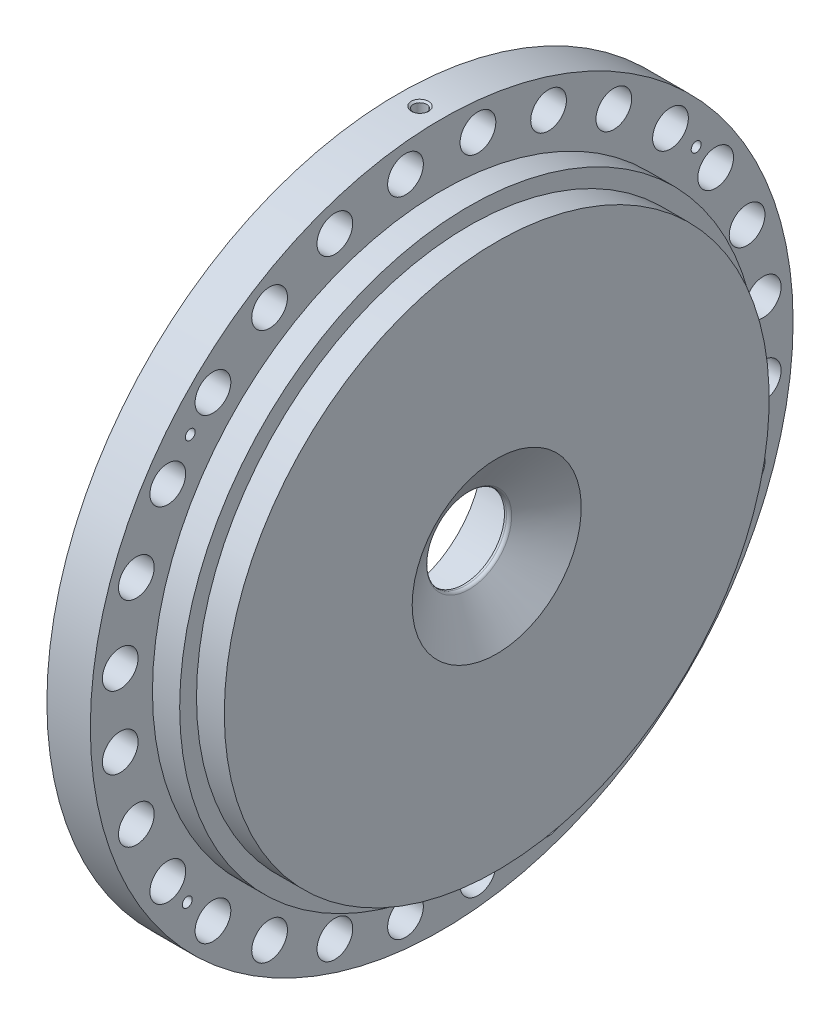
SolidWorks part; units mm, degrees
other "Markup1"
sketch "Sketch22" plane through (-5.9944, 281.051, 281.051) normal (-0.6486, 0.3883, 0.6546) x (0.7525, 0.1979, 0.6281)
material "CD4Mc-U Duplex Stainless Steel"
ref_plane "Front Plane" through (0, 0, 0) normal (0, 0, 1) x (1, 0, 0)
ref_plane "Top Plane" through (0, 0, 0) normal (0, 1, 0) x (1, 0, 0)
ref_plane "Right Plane" through (0, 0, 0) normal (1, 0, 0) x (0, 0, -1)
sketch "Sketch1" plane through (0, 0, 0) normal (0, 0, 1) x (1, 0, 0)
  line L13 (-5.9944, 67.5132) -> (-5.9944, 180.9496)
  line L14 (-5.9944, 281.051) -> (28.7528, 281.051)
  line L15 (28.7528, 281.051) -> (28.7528, 231.3686)
  line L16 (28.7528, 231.3686) -> (50.5206, 231.3686)
  line L17 (50.5206, 231.3686) -> (50.5206, 217.9066)
  line L18 (50.5206, 217.9066) -> (72.7456, 217.9066)
  line L19 (72.7456, 217.9066) -> (72.7456, 67.6275)
  line L22 (0, 0) -> (159.4613, 0) construction
  line L27 (-5.9944, 228.9937) -> (0, 228.9937)
  line L28 (0, 228.9937) -> (0, 180.9496)
  line L29 (0, 180.9496) -> (-5.9944, 180.9496)
  line L30 (-5.9944, 228.9937) -> (-5.9944, 281.051)
  line L32 (-5.9944, 67.5132) -> (46.4058, 67.5132)
  line L35 (46.4058, 67.5132) -> (46.4058, 32.5628)
  line L36 (46.4058, 32.5628) -> (48.0192, 32.5628)
  line L37 (50.6736, 33.9958) -> (72.7456, 67.6275)
  arc A0 (48.0192, 32.5628) -> (50.6736, 33.9958) centre (48.0192, 35.7378) ccw
  point P18 (49.7332, 32.5628)
  dimension "D10" = 3.175
  dimension "D1" = 78.74
  dimension "D2" = 43.9928
  dimension "D3" = 21.7678
  dimension "D4" = 3.3274
  dimension "D5" = 281.051
  dimension "D6" = 228.9937
  dimension "D7" = 231.3686
  dimension "D8" = 217.9066
  dimension "D9" = 180.9496
  dimension "D11" = 5.9944
  dimension "D12" = 32.5628
  dimension "D13" = 52.4002
  dimension "D14" = 67.5132
  dimension "D16" = 67.6275
revolve "Revolve1" add sketch "Sketch1" angle 360 about L22
sketch "Sketch4" plane through (-5.9944, 0, 0) normal (-1, 0, 0) x (0, 0, 1)
  line L0 (0, 0) -> (0, 281.051) construction
  line L1 (0, 0) -> (28.9721, 257.1355) construction
  circle A1 centre (28.9721, 257.1355) radius 14.2875
  circle A2 centre (0, 0) radius 258.7625 construction
  dimension "D2" = 28.575
  dimension "D3" = 517.525
  dimension "D1" = 6.429
extrude "Cut-Extrude1" cut sketch "Sketch4" against normal through all
pattern_circular "CirPattern2" count 28 over 360 about axis through (0, 0, 0) along (1, 0, 0) of "Cut-Extrude1"
sketch "Sketch5" plane through (0, 0, 0) normal (-1, 0, 0) x (0, 0, 1)
  line L0 (0, 0) -> (53.4138, 199.3429) construction
  line L2 (0, 0) -> (0, 281.051) construction
  circle A0 centre (0, 0) radius 206.375 construction
  circle A1 centre (53.4138, 199.3429) radius 9.525
  circle A3 centre (0, 0) radius 281.051 construction
  dimension "D1" = 412.75
  dimension "D3" = 19.05
  dimension "D2" = 15
hole_wizard "3/4-10 Tapped Hole1" positions "Sketch7" profile "Sketch8" tap size "3/4-10" standard "ANSI Inch"
sketch "Sketch7" plane through (0, 0, 0) normal (-1, 0, 0) x (0, 0, 1)
  point P0 (53.4138, 199.3429)
sketch "Sketch8" plane through (0, 199.3429, 53.4138) normal (0, 1, 0) x (0, 0, 1)
  line L0 (0, 0) -> (0, 30.4074)
  line L1 (0, 30.4074) -> (8.3337, 25.4)
  line L2 (8.3337, 25.4) -> (8.3337, 1.8263)
  line L3 (8.3337, 1.8263) -> (10.16, 0)
  line L5 (10.16, 0) -> (0, 0)
  line L6 (-8.3337, 1.8263) -> (-10.16, 0) construction
  line L10 (0, 30.4074) -> (-8.3337, 25.4) construction
  line L11 (0, -6.35) -> (0, 107.95) construction
  dimension "Tap Drill Dia." = 16.6675
  dimension "Tap Drill Depth" = 25.4
  dimension "Near C'Sink Dia." = 20.32
  dimension "Near C'Sink Angle" = 90
  dimension "Drill Angle" = 118
cosmetic thread "Hole Thread2" parameters "D1"=12.7, "D2"=19.05
pattern_circular "CirPattern3" count 12 over 360 about axis through (0, 0, 0) along (1, 0, 0) of "3/4-10 Tapped Hole1"
cosmetic thread "Hole Thread3" parameters "D1"=12.7, "D2"=19.05
cosmetic thread "Hole Thread4" parameters "D1"=12.7, "D2"=19.05
cosmetic thread "Hole Thread5" parameters "D1"=12.7, "D2"=19.05
cosmetic thread "Hole Thread6" parameters "D1"=12.7, "D2"=19.05
cosmetic thread "Hole Thread7" parameters "D1"=12.7, "D2"=19.05
cosmetic thread "Hole Thread8" parameters "D1"=12.7, "D2"=19.05
cosmetic thread "Hole Thread9" parameters "D1"=12.7, "D2"=19.05
cosmetic thread "Hole Thread10" parameters "D1"=12.7, "D2"=19.05
cosmetic thread "Hole Thread11" parameters "D1"=12.7, "D2"=19.05
cosmetic thread "Hole Thread12" parameters "D1"=12.7, "D2"=19.05
cosmetic thread "Hole Thread13" parameters "D1"=12.7, "D2"=19.05
sketch "Sketch9" plane through (-5.9944, 0, 0) normal (-1, 0, 0) x (0, 0, 1)
  line L0 (0, 0) -> (0, 94.996) construction
  line L1 (0, 0) -> (67.1723, 67.1723) construction
  circle A0 centre (0, 0) radius 94.996 construction
  circle A1 centre (67.1723, 67.1723) radius 11.1125
  dimension "D1" = 189.992
  dimension "D3" = 22.225
  dimension "D2" = 45
hole_wizard "7/8-9 Tapped Hole1" positions "3DSketch1" profile "Sketch10" tap size "7/8-9" standard "ANSI Inch"
sketch3d "3DSketch1"
  point P0 (-5.9944, 67.1723, 67.1723)
sketch "Sketch10" plane through (-5.9944, 67.1723, 67.1723) normal (0, 1, 0) x (0, 0, 1)
  line L0 (0, 0) -> (0, 31.2422)
  line L1 (0, 31.2422) -> (9.7231, 25.4)
  line L2 (9.7231, 25.4) -> (9.7231, 2.0244)
  line L3 (9.7231, 2.0244) -> (11.7475, 0)
  line L5 (11.7475, 0) -> (0, 0)
  line L6 (-9.7231, 2.0244) -> (-11.7475, 0) construction
  line L10 (0, 31.2422) -> (-9.7231, 25.4) construction
  line L11 (0, -6.35) -> (0, 107.95) construction
  dimension "Tap Drill Dia." = 19.4462
  dimension "Tap Drill Depth" = 25.4
  dimension "Near C'Sink Dia." = 23.495
  dimension "Near C'Sink Angle" = 90
  dimension "Drill Angle" = 118
cosmetic thread "Hole Thread14" parameters "D1"=44.45, "D2"=22.225
pattern_circular "CirPattern4" count 4 over 360 about axis through (0, 0, 0) along (1, 0, 0) of "7/8-9 Tapped Hole1"
cosmetic thread "Hole Thread15" parameters "D1"=44.45, "D2"=22.225
cosmetic thread "Hole Thread16" parameters "D1"=44.45, "D2"=22.225
cosmetic thread "Hole Thread17" parameters "D1"=44.45, "D2"=22.225
sketch "Sketch11" plane through (-5.9944, 0, 0) normal (-1, 0, 0) x (0, 0, 1)
  line L0 (0, 0) -> (201.0962, 162.8445) construction
  line L1 (0, 0) -> (258.7625, 0) construction
  circle A0 centre (0, 0) radius 258.7625 construction
  circle A2 centre (201.0962, 162.8445) radius 4.7625
  dimension "D1" = 517.525
  dimension "D3" = 9.525
  dimension "D2" = 39
hole_wizard "Tap Drill for 3/8-16 Tap1" positions "3DSketch9" profile "Sketch21" hole size "3/8-16" standard "ANSI Inch"
sketch3d "3DSketch9"
  point P0 (-5.9944, 162.8445, 201.0962)
sketch "Sketch21" plane through (-5.9944, 162.8445, 201.0962) normal (0, 1, 0) x (0, 0, 1)
  line L0 (0, 0) -> (0, 43.0247)
  line L1 (0, 43.0247) -> (3.9687, 40.64)
  line L2 (3.9687, 40.64) -> (3.9687, 0.635)
  line L3 (3.9687, 0.635) -> (4.6037, 0)
  line L5 (4.6037, 0) -> (0, 0)
  line L6 (-3.9687, 0.635) -> (-4.6037, 0) construction
  line L10 (0, 43.0247) -> (-3.9688, 40.64) construction
  line L11 (0, -6.35) -> (0, 107.95) construction
  dimension "Hole Dia." = 7.9375
  dimension "Hole Depth" = 40.64
  dimension "Near C'Sink Dia." = 9.2075
  dimension "Near C'Sink Angle" = 90
  dimension "Drill Angle" = 118
ref_plane "Plane2" through (0, 281.051, 0) normal (0, 1, 0) x (1, 0, 0)
sketch "Sketch20" plane through (0, 281.051, 0) normal (0, 1, 0) x (1, 0, 0)
  line L0 (-5.9944, 0) -> (11.3792, 0) construction
  line L1 (-5.9944, 281.051) -> (-5.9944, -281.051) construction
  dimension "D1" = 17.3736
pattern_circular "CirPattern5" count 56 over 360 about axis through (0, 0, 0) along (-1, 0, 0) skipping 1, 2, 3, 4, 5, 6, 7, 8, 9, 10, 11, 12, 13, 14, 15, 17, 18, 19, 20, 21, 22, 23, 24, 25, 26, 27, 29, 30, 31, 32, 33, 34, 35, 36, 37, 38, 39, 40, 41, 42, 43, 45, 46, 47, 48, 49, 50, 51, 52, 53, 54, 55 of "Tap Drill for 3/8-16 Tap1"
hole_wizard "1/2-13 Tapped Hole4" positions "3DSketch8" profile "Sketch19" tap size "1/2-13" standard "ANSI Inch"
sketch3d "3DSketch8"
  point P0 (11.3792, 281.051, 0)
sketch "Sketch19" plane through (11.3792, 281.051, 0) normal (1, 0, 0) x (0, 0, 1)
  line L0 (0, 0) -> (0, 38.2715)
  line L1 (0, 38.2715) -> (5.3581, 35.052)
  line L2 (5.3581, 35.052) -> (5.3581, 1.3651)
  line L3 (5.3581, 1.3651) -> (6.985, 0)
  line L5 (6.985, 0) -> (0, 0)
  line L6 (-5.3581, 1.3651) -> (-6.985, 0) construction
  line L10 (0, 38.2715) -> (-5.3581, 35.052) construction
  line L11 (0, -6.35) -> (0, 107.95) construction
  dimension "Tap Drill Dia." = 10.7163
  dimension "Tap Drill Depth" = 35.052
  dimension "Near C'Sink Dia." = 13.97
  dimension "Near C'Sink Angle" = 100
  dimension "Drill Angle" = 118
cosmetic thread "Hole Thread24" parameters "D1"=25.4, "D2"=12.7
